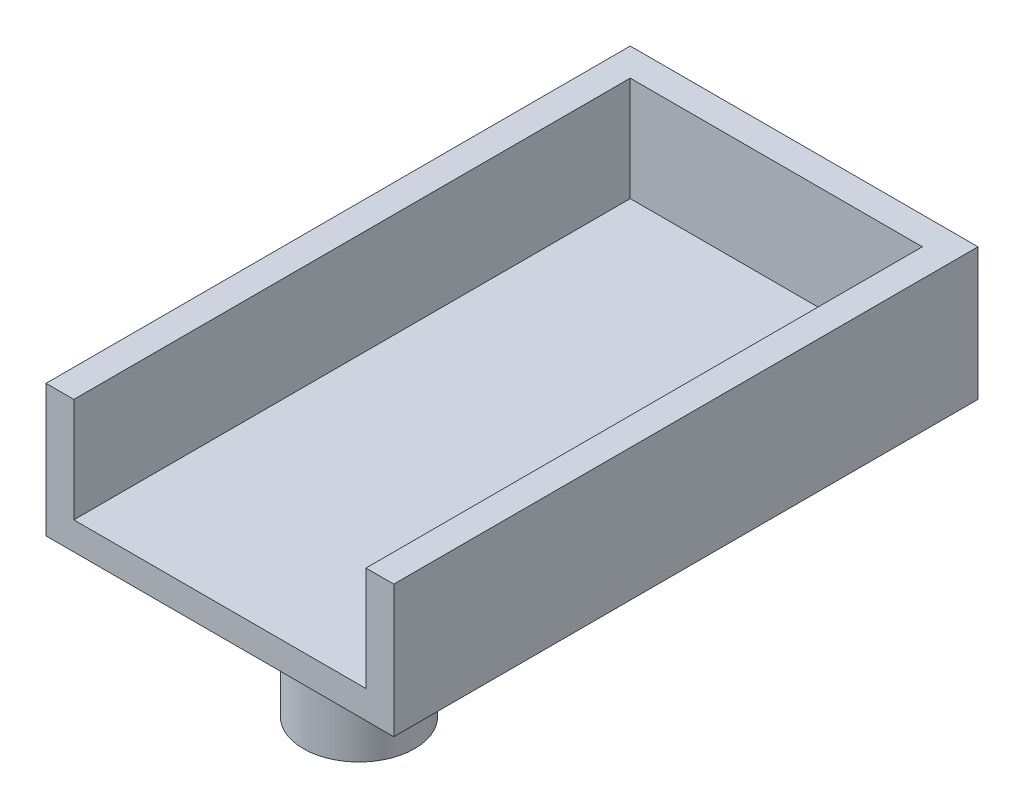
SolidWorks part; units mm, degrees
ref_plane "Front Plane" through (0, 0, 0) normal (0, 0, 1) x (1, 0, 0)
ref_plane "Top Plane" through (0, 0, 0) normal (0, 1, 0) x (1, 0, 0)
ref_plane "Right Plane" through (0, 0, 0) normal (1, 0, 0) x (0, 0, -1)
sketch "Sketch1" plane through (0, 0, 0) normal (0, 1, 0) x (1, 0, 0)
  line L1 (0, 40) -> (25, 40)
  line L2 (0, 40) -> (0, 0)
  line L3 (0, 0) -> (25, 0)
  line L4 (25, 40) -> (25, 0)
  dimension "D1" = 25
  dimension "D2" = 40
extrude "Boss-Extrude1" add sketch "Sketch1" along normal blind 2
sketch "Sketch2" plane through (0, 2, 0) normal (0, 1, 0) x (1, 0, 0)
  line L0 (25, 40) -> (0, 40) construction
  line L1 (0, 0) -> (2, 0)
  line L2 (0, 0) -> (0, 40)
  line L3 (0, 40) -> (2, 40)
  line L4 (2, 0) -> (2, 40)
  line L5 (0, 0) -> (25, 0) construction
  line L6 (25, 40) -> (23, 40)
  line L7 (25, 40) -> (25, 0)
  line L8 (25, 0) -> (23, 0)
  line L9 (23, 40) -> (23, 0)
  dimension "D1" = 2
  dimension "D2" = 2
extrude "Boss-Extrude2" add sketch "Sketch2" along normal blind 7.5
sketch "Sketch3" plane through (0, 0, 0) normal (0, -1, 0) x (-1, 0, 0)
  line L0 (0, 0) -> (-25, 0) construction
  circle A0 centre (-12.5, 10) radius 4
  point P2 (-12.5, 0)
  dimension "D1" = 8
  dimension "D2" = 10
extrude "Boss-Extrude3" add sketch "Sketch3" along normal blind 10
sketch "Sketch4" plane through (0, 0, -40) normal (0, 0, -1) x (-1, 0, 0)
  line L1 (-25, 9.5) -> (0, 9.5)
  line L2 (-25, 9.5) -> (-25, 0)
  line L3 (-25, 0) -> (0, 0)
  line L4 (0, 9.5) -> (0, 0)
extrude "Boss-Extrude4" add sketch "Sketch4" along normal blind 2 contours L1 L4 L3 L2
